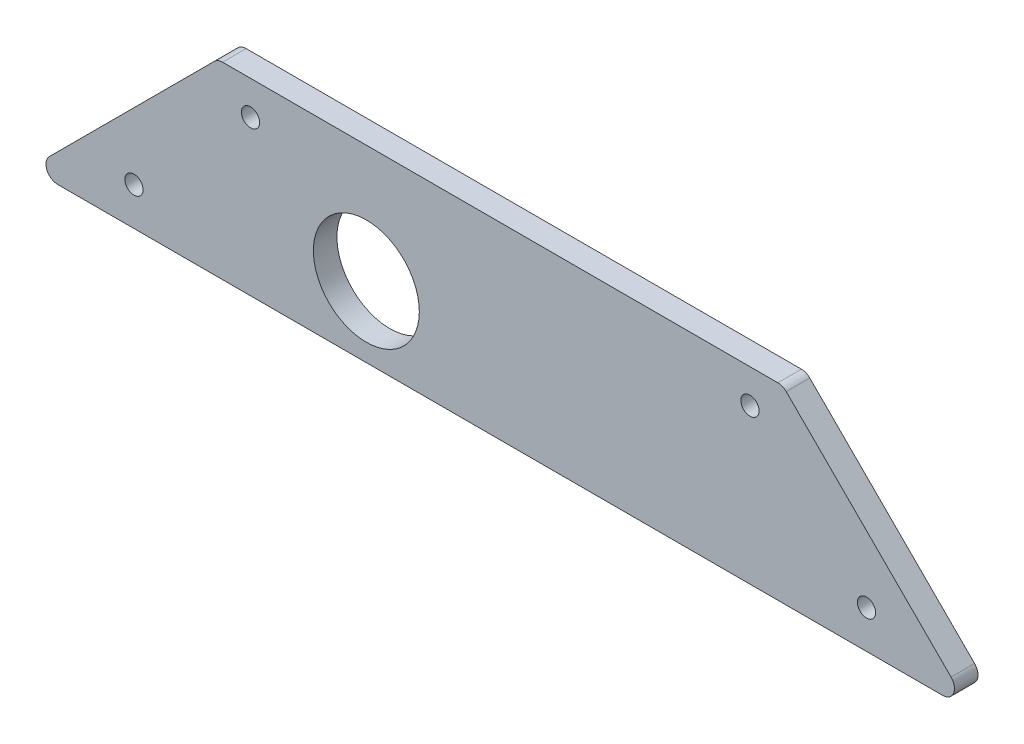
SolidWorks part; units mm, degrees
material "6061-T6 (SS)"
ref_plane "Front Plane" through (0, 0, 0) normal (0, 0, 1) x (1, 0, 0)
ref_plane "Top Plane" through (0, 0, 0) normal (0, 1, 0) x (1, 0, 0)
ref_plane "Right Plane" through (0, 0, 0) normal (1, 0, 0) x (0, 0, -1)
sketch "Sketch1" plane through (0, 0, 0) normal (0, 0, 1) x (1, 0, 0)
  line L0 (-76.2, 29.1622) -> (-127, -21.6378)
  line L1 (-76.2, 29.1622) -> (76.2, 29.1622)
  line L2 (-127, -21.6378) -> (127, -21.6378)
  line L3 (127, -21.6378) -> (76.2, 29.1622)
  point P0 (0, 0)
  point P1 (0, -21.6378)
  dimension "D1" = 135
  dimension "D2" = 254
  dimension "D3" = 50.8
  dimension "D4" = 135
extrude "Boss-Extrude1" add sketch "Sketch1" along normal mid plane 6.35
sketch "Sketch2" plane through (0, 0, 3.175) normal (0, 0, 1) x (1, 0, 0)
  line L0 (-127, -21.6378) -> (127, -21.6378) construction
  line L3 (-76.2, 29.1622) -> (-127, -21.6378) construction
  circle A0 centre (-36.108, -2.5878) radius 14.2875
  dimension "D1" = 19.05
  dimension "D2" = 28.575
  dimension "D3" = 50.8
extrude "Cut-Extrude1" cut sketch "Sketch2" against normal through all
sketch "Sketch8" plane through (0, 0, 3.175) normal (0, 0, 1) x (1, 0, 0)
  line L0 (0, 105.3622) -> (-327.0287, -221.6666) construction
  line L1 (0, 69.4411) -> (279.7642, -210.3231) construction
  line L2 (76.2, 29.1622) -> (297.7247, -192.3626) construction
  line L3 (0, 69.4411) -> (-309.0682, -239.6271) construction
  line L4 (76.2, 29.1622) -> (0, 105.3622) construction
  line L5 (14.5597, 84.0009) -> (-309.0682, -239.6271) construction
  line L6 (58.2395, 11.2016) -> (279.7642, -210.3231) construction
  line L7 (-3.4008, 101.9614) -> (-327.0287, -221.6666) construction
  line L8 (98.7828, -11.3812) -> (67.3519, 20.0497) construction
  line L9 (-76.2, 29.1622) -> (-127, -21.6378) construction
  point P2 (67.3519, 20.0497)
  point P6 (98.7828, -11.3812)
  point P16 (-67.3519, 20.0497)
  point P18 (-98.7828, -11.3812)
  dimension "D1" = 25.4
  dimension "D2" = 25.4
  dimension "D3" = 12.7
  dimension "D4" = 107.95
  dimension "D5" = 44.45
  dimension "D6" = 12.7
  dimension "D7" = 12.7
  dimension "D8" = 107.95
  dimension "D9" = 12.7
  dimension "D10" = 44.45
hole_wizard "#10 (0.1935) Diameter Hole2" positions "3DSketch1" profile "Sketch9" hole size "#10" standard "ANSI Inch" end condition through all
sketch3d "3DSketch1"
  line L0 (-127, -21.6378, 3.175) -> (-76.2, 29.1622, 3.175) construction
  line L2 (-76.2, 29.1622, 3.175) -> (0, 105.3622, 3.175) construction
  line L3 (0, 105.3622, 3.175) -> (145.7507, -40.3886, 3.175) construction
  line L4 (76.2, 29.1622, 3.175) -> (297.7247, -192.3626, 3.175) construction
  line L5 (145.7507, -40.3886, 3.175) -> (127.7902, -58.3491, 3.175) construction
  line L6 (0, 69.4411, 3.175) -> (279.7642, -210.3231, 3.175) construction
  line L7 (127.7902, -58.3491, 3.175) -> (0, 69.4411, 3.175) construction
  line L8 (0, 69.4411, 3.175) -> (-116.7666, -47.3254, 3.175) construction
  line L9 (0, 69.4411, 3.175) -> (-309.0682, -239.6271, 3.175) construction
  line L10 (-116.7666, -47.3254, 3.175) -> (-134.7271, -29.3649, 3.175) construction
  line L11 (0, 105.3622, 3.175) -> (-327.0287, -221.6666, 3.175) construction
  line L12 (-134.7271, -29.3649, 3.175) -> (-127, -21.6378, 3.175) construction
  point P0 (67.3519, 20.0497, 3.175)
  point P4 (98.7828, -11.3812, 3.175)
  point P8 (-67.3519, 20.0497, 3.175)
  point P34 (-98.7828, -11.3812, 3.175)
  dimension "D1" = 12.7
  dimension "D2" = 107.95
  dimension "D3" = 12.7
  dimension "D6" = 12.7
  dimension "D4" = 107.95
  dimension "D5" = 44.45
sketch "Sketch9" plane through (67.3519, 20.0497, 3.175) normal (1, 0, 0) x (0, -1, 0)
  line L0 (0, 0) -> (0, 6.35)
  line L1 (0, 6.35) -> (2.4574, 6.35)
  line L2 (2.4574, 6.35) -> (2.4574, 0)
  line L5 (2.4574, 0) -> (0, 0)
  line L11 (0, -6.35) -> (0, 107.95) construction
  dimension "Thru Hole Dia." = 4.9149
  dimension "Thru Hole Depth" = 6.35
fillet "Fillet1" radius 3.175 4 edges at (-127, -21.6378, 0) (-76.2, 29.1622, 0) (127, -21.6378, 0) (76.2, 29.1622, 0)
